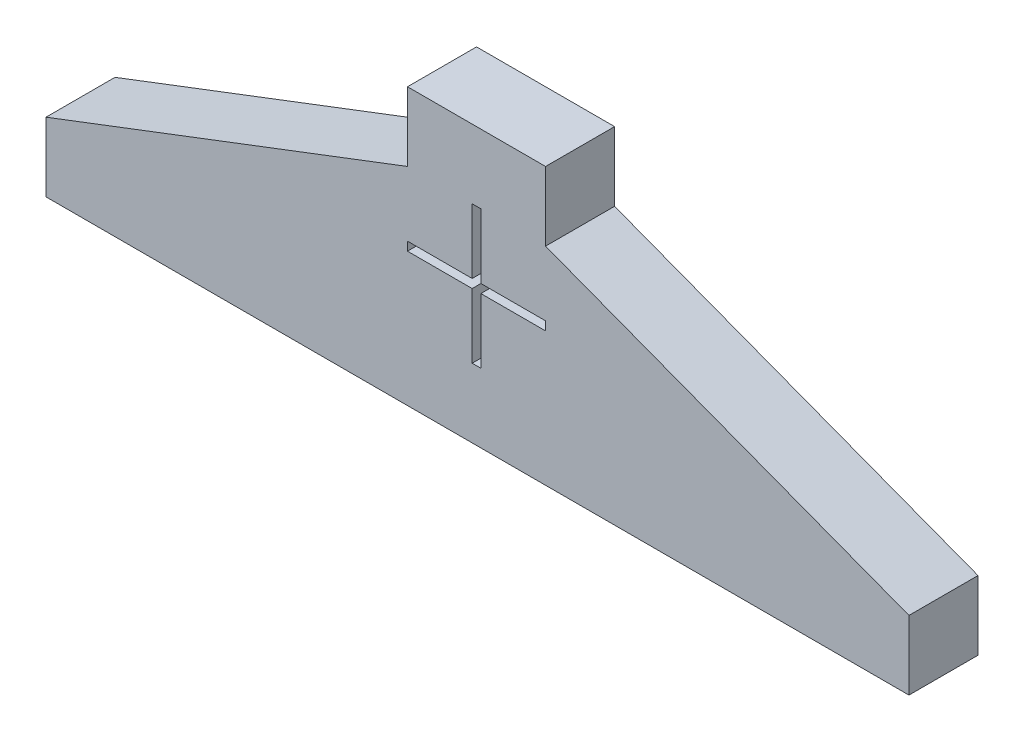
SolidWorks part; units mm, degrees
ref_plane "Front Plane" through (0, 0, 0) normal (0, 0, 1) x (1, 0, 0)
ref_plane "Top Plane" through (0, 0, 0) normal (0, 1, 0) x (1, 0, 0)
ref_plane "Right Plane" through (0, 0, 0) normal (1, 0, 0) x (0, 0, -1)
sketch "Sketch1" plane through (0, 0, 0) normal (0, 1, 0) x (1, 0, 0)
  line L1 (-19.845, 1.5875) -> (19.845, 1.5875)
  line L2 (-19.845, 1.5875) -> (-19.845, -1.5875)
  line L3 (-19.845, -1.5875) -> (19.845, -1.5875)
  line L4 (19.845, 1.5875) -> (19.845, -1.5875)
  line L5 (-19.845, 1.5875) -> (19.845, -1.5875) construction
  line L6 (-19.845, -1.5875) -> (19.845, 1.5875) construction
  point P0 (0, 0)
  dimension "D1" = 3.175
  dimension "D2" = 39.69
extrude "Boss-Extrude1" add sketch "Sketch1" along normal blind 12.7
ref_plane "Plane1" through (0, 0, 1.5875) normal (0, 0, 1) x (1, 0, 0)
sketch "Sketch2" plane through (0, 0, 1.5875) normal (0, 0, 1) x (1, 0, 0)
  line L0 (-3.2189, 12.7) -> (3.1311, 12.7)
  line L2 (3.1311, 12.7) -> (3.1311, 9.525)
  line L3 (-3.2189, 9.525) -> (3.1311, 9.525)
  line L4 (-3.2189, 12.7) -> (-3.2189, 9.525)
  line L5 (-19.845, 0) -> (-19.845, 3.175)
  line L7 (19.7572, 0) -> (19.7572, 3.175)
  line L8 (-19.845, 3.175) -> (-3.2189, 9.525)
  line L9 (3.1311, 9.525) -> (19.7572, 3.175)
  line L10 (-19.845, 12.7) -> (-19.845, 3.175)
  line L11 (-19.845, 12.7) -> (-3.2189, 12.7)
  line L12 (3.1311, 12.7) -> (19.845, 12.7)
  line L13 (19.845, 12.7) -> (19.7572, 3.175)
  point P5 (-0.0439, 12.7)
  dimension "D1" = 6.35
  dimension "D2" = 3.175
  dimension "D3" = 3.175
sketch "Sketch3" plane through (0, 0, 1.5875) normal (0, 0, 1) x (1, 0, 0)
  line L3 (3.1311, 6.15) -> (3.1311, 6.55)
  line L4 (-3.2189, 6.15) -> (-3.2189, 6.55)
  line L5 (-3.2189, 6.55) -> (3.1311, 6.55)
  line L6 (3.1311, 6.15) -> (-3.2189, 6.15)
  line L7 (-0.2439, 9.525) -> (0.1561, 9.525)
  line L8 (0.1561, 9.525) -> (0.1561, 3.175)
  line L9 (0.1561, 3.175) -> (-0.2439, 3.175)
  line L10 (-0.2439, 3.175) -> (-0.2439, 9.525)
  point P9 (-0.0439, 6.35)
  point P15 (-0.0439, 9.525)
extrude "Cut-Extrude7" cut sketch "Sketch3" against normal blind 3.175 contours L10 L5 L8 L7 | L10 L9 L8 L6
sketch "Sketch6" plane through (0, 0, 1.5875) normal (0, 0, 1) x (1, 0, 0)
  line L0 (3.1311, 12.7) -> (3.1311, 9.525)
  line L1 (19.845, 0) -> (19.845, 3.175)
  line L2 (19.845, 12.7) -> (19.845, 0) construction
  line L3 (3.1311, 9.525) -> (19.845, 3.175)
  line L4 (19.845, 0) -> (-19.845, 0)
  line L5 (-19.845, 0) -> (-19.845, 3.175)
  line L6 (-19.845, 3.175) -> (-3.2189, 9.525)
  line L7 (-3.2189, 9.525) -> (-3.2189, 12.7)
  line L8 (-3.2189, 12.7) -> (3.1311, 12.7)
  line L9 (3.1311, 12.7) -> (19.845, 12.7)
  line L10 (19.845, 12.7) -> (19.845, 3.175)
  line L11 (-3.2189, 12.7) -> (-19.845, 12.7)
  line L12 (-19.845, 12.7) -> (-19.845, 3.175)
  line M15 (19.845, 0) -> (19.845, 12.7)
  line M16 (19.845, 12.7) -> (-19.845, 12.7)
  line M17 (-19.845, 12.7) -> (-19.845, 0)
  dimension "D1" = 3.175
extrude "Cut-Extrude8" cut sketch "Sketch6" against normal blind 3.175 contours L6 L7 M16 M17 | L0 L3 M15 M16
